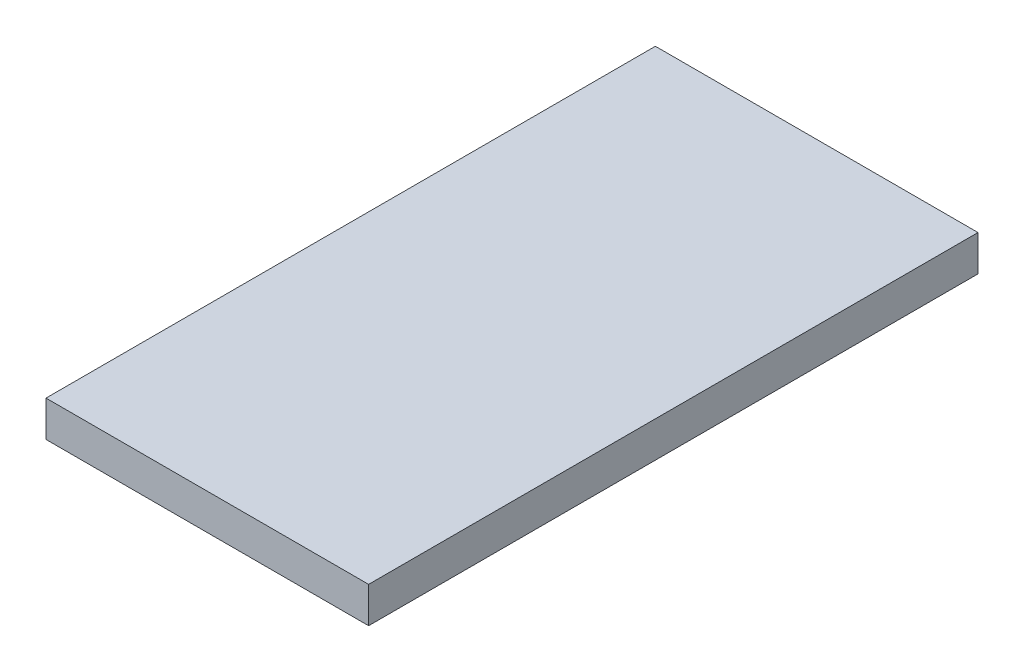
SolidWorks part; units mm, degrees
ref_plane "Front Plane" through (0, 0, 0) normal (0, 0, 1) x (1, 0, 0)
ref_plane "Top Plane" through (0, 0, 0) normal (0, 1, 0) x (1, 0, 0)
ref_plane "Right Plane" through (0, 0, 0) normal (1, 0, 0) x (0, 0, -1)
other "Configuration Table"
sketch "Sketch1" plane through (0, 0, 0) normal (0, 0, 1) x (1, 0, 0)
  line L1 (-90, 0) -> (90, 0)
  line L2 (-90, 0) -> (-90, 20)
  line L3 (-90, 20) -> (90, 20)
  line L4 (90, 0) -> (90, 20)
extrude "UCY_taban_180x20x340_1" add sketch "Sketch1" against normal blind 340 separate body
